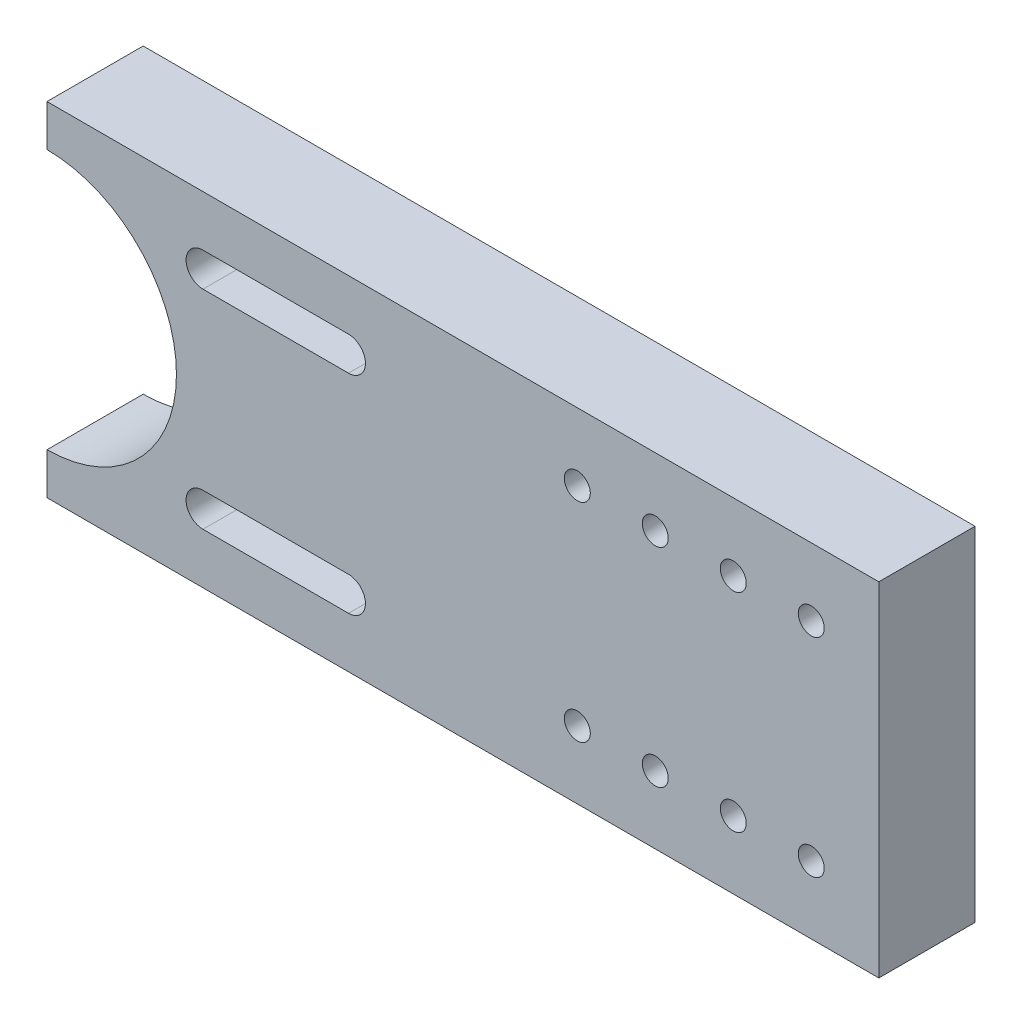
SolidWorks part; units mm, degrees
material "SKD11淬火HRC56-60"
ref_plane "前基準面" through (0, 0, 0) normal (0, 0, 1) x (1, 0, 0)
ref_plane "上基準面" through (0, 0, 0) normal (0, 1, 0) x (1, 0, 0)
ref_plane "右基準面" through (0, 0, 0) normal (1, 0, 0) x (0, 0, -1)
sketch "草图1" plane through (0, 0, 0) normal (0, 0, 1) x (1, 0, 0)
  line L1 (0, 0) -> (160, 0)
  line L2 (0, 0) -> (0, 66)
  line L3 (0, 66) -> (160, 66)
  line L4 (160, 0) -> (160, 66)
  dimension "D1" = 66
  dimension "D2" = 160
extrude "凸台-拉伸1" add sketch "草图1" along normal blind 18.5
sketch "草图2" plane through (0, 0, 18.5) normal (0, 0, 1) x (1, 0, 0)
  line L1 (0, 33) -> (-25.6298, 33) construction
  line L2 (0, 66) -> (0, 0) construction
  circle A0 centre (-0.1, 33) radius 25
  dimension "D1" = 50
  dimension "D2" = 0.1
extrude "切除-拉伸1" cut sketch "草图2" against normal blind 20
hole_wizard "M6 螺纹孔1" positions "草图6" profile "草图5" tap size "M6" standard "ISO" end condition through all
sketch "草图6" plane through (0, 0, 0) normal (0, 0, -1) x (-1, 0, 0)
  line L0 (-160, 33) -> (-66.3793, 33) construction
  line L1 (-160, 0) -> (-160, 66) construction
  point P3 (-147, 53)
  point P5 (-147, 13)
  dimension "D1" = 40
  dimension "D2" = 13
cosmetic thread "孔螺蚊线1" parameters "D2"=6
cosmetic thread "孔螺蚊线2" parameters "D2"=6
sketch "草图5" plane through (147, 53, 0) normal (1, 0, 0) x (0, 1, 0)
  line L0 (0, 0) -> (0, 18.5)
  line L1 (0, 18.5) -> (2.5, 18.5)
  line L2 (2.5, 18.5) -> (2.5, 0)
  line L5 (2.5, 0) -> (0, 0)
  line L11 (0, -6.35) -> (0, 107.95) construction
  dimension "通孔螺纹孔钻头直径" = 5
  dimension "通孔螺纹孔钻头深度" = 18.5
pattern_linear "阵列(线性)1" count 4 spacing 15 along (-1, 0, 0) of "M6 螺纹孔1"
sketch "草图7" plane through (0, 0, 0) normal (0, 0, -1) x (-1, 0, 0)
  line L0 (-30, 53) -> (-58, 53) construction
  line L1 (-30, 49.75) -> (-58, 49.75)
  line L2 (-30, 56.25) -> (-58, 56.25)
  line L3 (-24.9, 33) -> (-66.3972, 33) construction
  line L4 (-30, 13) -> (-58, 13) construction
  line L5 (-30, 16.25) -> (-58, 16.25)
  line L6 (-30, 9.75) -> (-58, 9.75)
  line L7 (0, 66) -> (0, 57.9998) construction
  arc A0 (-30, 49.75) -> (-30, 56.25) centre (-30, 53) ccw
  arc A1 (-58, 56.25) -> (-58, 49.75) centre (-58, 53) ccw
  arc A2 (0, 57.9998) -> (0, 8.0002) centre (0.1, 33) ccw construction
  arc A3 (-30, 16.25) -> (-30, 9.75) centre (-30, 13) cw
  arc A4 (-58, 9.75) -> (-58, 16.25) centre (-58, 13) cw
  point P2 (-44, 53)
  point P15 (-44, 13)
  dimension "D1" = 30
  dimension "D2" = 6.5
  dimension "D3" = 28
  dimension "D4" = 40
extrude "切除-拉伸4" cut sketch "草图7" against normal blind 40
hole_wizard "M4 螺纹孔1" positions "草图9" profile "草图8" tap size "M4" standard "ISO"
sketch "草图9" plane through (0, 0, 0) normal (-1, 0, 0) x (0, 0, 1)
  point P0 (4.75, 5)
  point P1 (13.75, 5)
  point P4 (4.75, 61)
  point P7 (13.75, 61)
sketch "草图8" plane through (0, 5, 4.75) normal (0, 1, 0) x (0, 0, 1)
  line L0 (0, 0) -> (0, 11.0914)
  line L1 (0, 11.0914) -> (1.65, 10.1)
  line L2 (1.65, 10.1) -> (1.65, 0)
  line L5 (1.65, 0) -> (0, 0)
  line L10 (0, 11.0914) -> (-1.65, 10.1) construction
  line L11 (0, -6.35) -> (0, 107.95) construction
  dimension "螺纹孔钻头直径" = 3.3
  dimension "螺纹孔钻头深度" = 10.1
  dimension "导头角度" = 118
cosmetic thread "孔螺蚊线3" parameters "D1"=8, "D2"=4
cosmetic thread "孔螺蚊线4" parameters "D1"=8, "D2"=4
cosmetic thread "孔螺蚊线5" parameters "D1"=8, "D2"=4
cosmetic thread "孔螺蚊线6" parameters "D1"=8, "D2"=4
